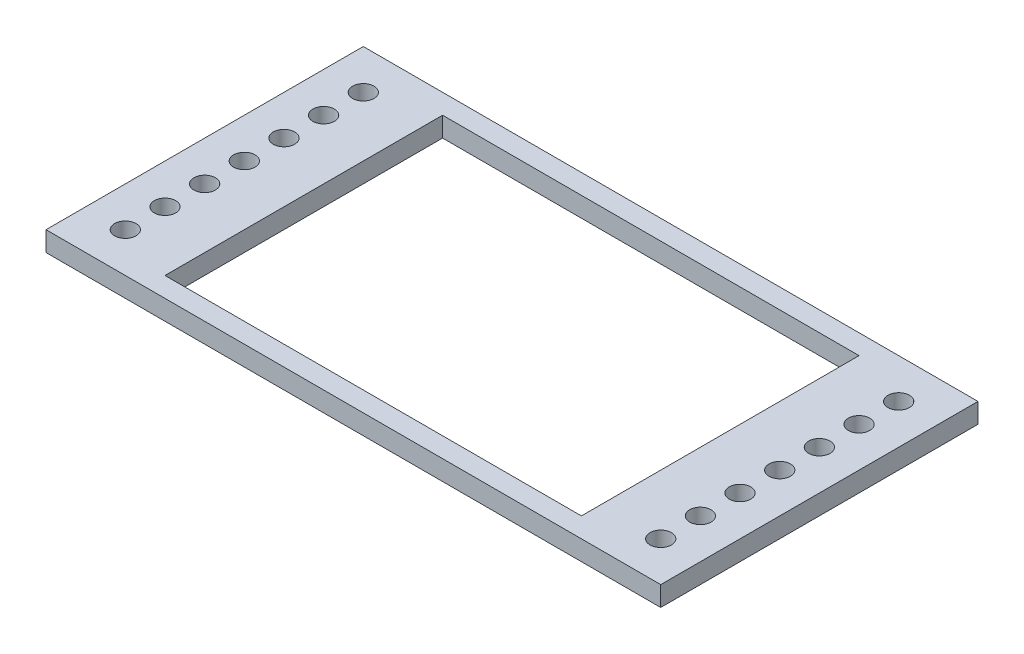
SolidWorks part; units mm, degrees
ref_plane "Front Plane" through (0, 0, 0) normal (0, 0, 1) x (1, 0, 0)
ref_plane "Top Plane" through (0, 0, 0) normal (0, 1, 0) x (1, 0, 0)
ref_plane "Right Plane" through (0, 0, 0) normal (1, 0, 0) x (0, 0, -1)
sketch "Sketch1" plane through (0, 0, 0) normal (0, 1, 0) x (1, 0, 0)
  line L1 (-66.675, -44.45) -> (66.675, -44.45)
  line L2 (-66.675, -44.45) -> (-66.675, 44.45)
  line L3 (-66.675, 44.45) -> (66.675, 44.45)
  line L4 (66.675, -44.45) -> (66.675, 44.45)
  line L5 (-66.675, -44.45) -> (66.675, 44.45) construction
  line L6 (-66.675, 44.45) -> (66.675, -44.45) construction
  line L7 (-98.425, -50.8) -> (98.425, -50.8)
  line L8 (-98.425, -50.8) -> (-98.425, 50.8)
  line L9 (-98.425, 50.8) -> (98.425, 50.8)
  line L10 (98.425, -50.8) -> (98.425, 50.8)
  line L11 (-98.425, -50.8) -> (98.425, 50.8) construction
  line L12 (-98.425, 50.8) -> (98.425, -50.8) construction
  circle A0 centre (-85.725, 38.1) radius 3.429
  circle A1 centre (85.725, 38.1) radius 3.429
  circle A2 centre (85.725, 25.4) radius 3.429
  circle A3 centre (85.725, 12.7) radius 3.429
  circle A4 centre (85.725, 0) radius 3.429
  circle A5 centre (85.725, -12.7) radius 3.429
  circle A6 centre (85.725, -25.4) radius 3.429
  circle A7 centre (85.725, -38.1) radius 3.429
  circle A8 centre (-85.725, 25.4) radius 3.429
  circle A9 centre (-85.725, 12.7) radius 3.429
  circle A10 centre (-85.725, 0) radius 3.429
  circle A11 centre (-85.725, -12.7) radius 3.429
  circle A12 centre (-85.725, -25.4) radius 3.429
  circle A13 centre (-85.725, -38.1) radius 3.429
  point P0 (0, 0)
  point P6 (0, 0)
  dimension "D5" = 6.858
  dimension "D1" = 133.35
  dimension "D2" = 88.9
  dimension "D3" = 101.6
  dimension "D4" = 196.85
  dimension "D6" = 12.7
  dimension "D7" = 12.7
  dimension "D10" = 171.45
  dimension "D8" = 2
  dimension "D9" = 7
extrude "Boss-Extrude1" add sketch "Sketch1" along normal blind 6.35
